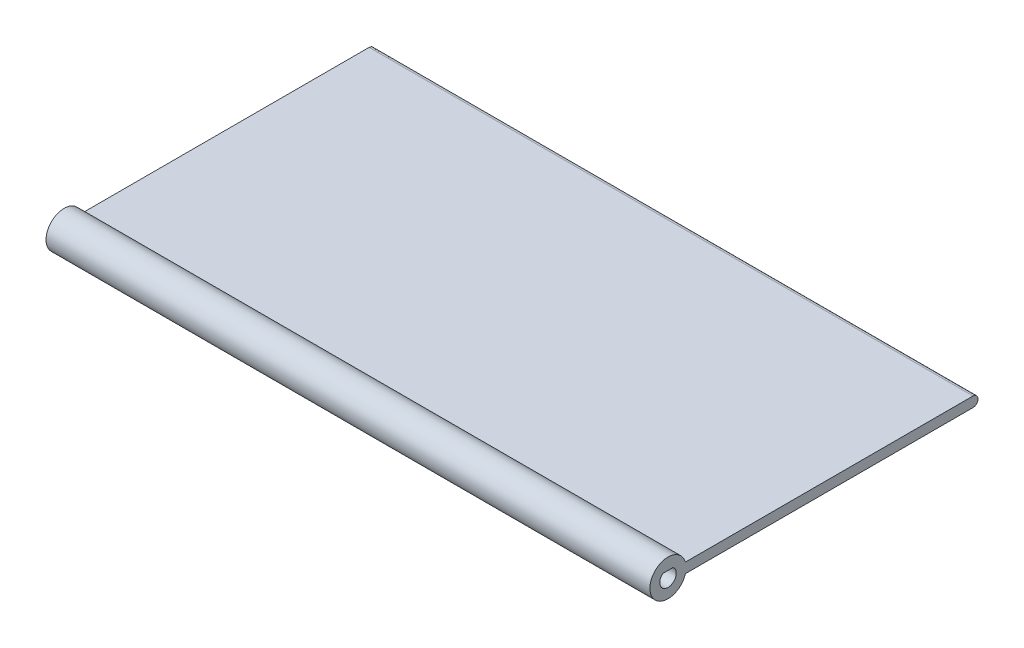
SolidWorks part; units mm, degrees
material "PLA - Approx"
ref_plane "Front Plane" through (0, 0, 0) normal (0, 0, 1) x (1, 0, 0)
ref_plane "Top Plane" through (0, 0, 0) normal (0, 1, 0) x (1, 0, 0)
ref_plane "Right Plane" through (0, 0, 0) normal (1, 0, 0) x (0, 0, -1)
other "Center of Mass"
sketch "Sketch1" plane through (0, 0, 0) normal (1, 0, 0) x (0, 0, -1)
  circle A0 centre (0, 0) radius 9
  dimension "D1" = 18
extrude "Boss-Extrude1" add sketch "Sketch1" along normal blind 300
sketch "Sketch2" plane through (300, 0, 0) normal (1, 0, 0) x (0, 0, -1)
  line L0 (-2.5632, 3.2) -> (2.5632, 3.2)
  arc A0 (-2.5632, 3.2) -> (2.5632, 3.2) centre (0, 0) ccw
  dimension "D2" = 8.2
  dimension "D1" = 3.2
extrude "Cut-Extrude1" cut sketch "Sketch2" against normal through all both and the other way through all
sketch "Sketch3" plane through (300, 0, 0) normal (1, 0, 0) x (0, 0, -1)
  line L1 (4.1, 2.5) -> (154, 2.5)
  line L2 (4.1, 2.5) -> (4.1, -2.5)
  line L3 (4.1, -2.5) -> (154, -2.5)
  line L4 (154, 2.5) -> (154, -2.5)
  arc A0 (-2.5632, 3.2) -> (2.5632, 3.2) centre (0, 0) ccw construction
  circle A1 centre (0, 0) radius 9 construction
  dimension "D1" = 154
  dimension "D2" = 5
  dimension "D3" = 2.5
extrude "Boss-Extrude2" add sketch "Sketch3" against normal up to surface (300 mm away) up to face at (0, -0.45, 0)
sketch "Sketch4" plane through (300, 0, 0) normal (1, 0, 0) x (0, 0, -1)
  line L0 (154, 2.5) -> (8.6458, 2.5) construction
  line L1 (8.6458, -2.5) -> (154, -2.5) construction
  line L2 (154, -2.5) -> (154, 2.5) construction
  line L3 (151.5, 2.5) -> (154, 2.5)
  line L4 (154, 2.5) -> (154, -2.5)
  line L5 (154, -2.5) -> (151.5, -2.5)
  arc A0 (151.5, -2.5) -> (151.5, 2.5) centre (151.5, 0) ccw
  line M5 (8.6458, -2.5) -> (154, -2.5)
  line M6 (154, -2.5) -> (154, 2.5)
  line M7 (154, 2.5) -> (8.6458, 2.5)
extrude "Cut-Extrude2" cut sketch "Sketch4" against normal through all both and the other way through all contours A0 L4 M7 | A0 M5 M6
equation "\"D3@Sketch3\"=\"D2@Sketch3\"/2"
